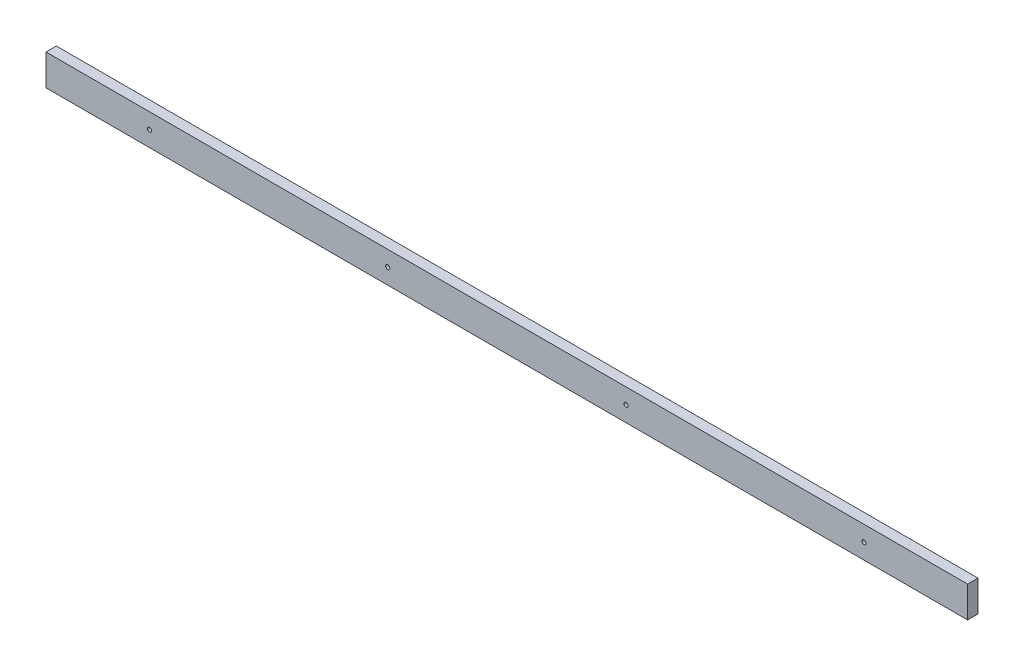
SolidWorks part; units mm, degrees
ref_plane "Спереди" through (0, 0, 0) normal (0, 0, 1) x (1, 0, 0)
ref_plane "Сверху" through (0, 0, 0) normal (0, 1, 0) x (1, 0, 0)
ref_plane "Справа" through (0, 0, 0) normal (1, 0, 0) x (0, 0, -1)
sketch "Эскиз1" plane through (0, 0, 0) normal (0, 0, 1) x (1, 0, 0)
  line L1 (-890, 30) -> (890, 30)
  line L2 (-890, 30) -> (-890, -30)
  line L3 (-890, -30) -> (890, -30)
  line L4 (890, 30) -> (890, -30)
  line L5 (-890, 30) -> (890, -30) construction
  line L6 (-890, -30) -> (890, 30) construction
  point P0 (0, 0)
  dimension "D1" = 1780
  dimension "D2" = 60
extrude "Бобышка-Вытянуть1" add sketch "Эскиз1" along normal mid plane 20
sketch "Эскиз2" plane through (0, 0, 0) normal (0, 0, 1) x (1, 0, 0)
  line L0 (-890, 0) -> (890, 0) construction
  line L1 (-890, 30) -> (-890, -30) construction
  line L2 (0, 174.5853) -> (0, -190.4559) construction
  line L3 (890, -30) -> (890, 30) construction
  line L4 (-690, 220.3832) -> (-690, -190.4559) construction
  line L5 (-230, 220.3832) -> (-230, -190.4559) construction
  circle A0 centre (-690, 0) radius 4
  circle A1 centre (-230, 0) radius 4
  circle A4 centre (230, 0) radius 4
  circle A5 centre (690, 0) radius 4
  dimension "D2" = 8
  dimension "D1" = 200
  dimension "D3" = 690
  dimension "D4" = 460
extrude "Вырез-Вытянуть1" cut sketch "Эскиз2" against normal through all and the other way through all
equation "\"D4@Эскиз2\"=2*\"D3@Эскиз2\"/3"
